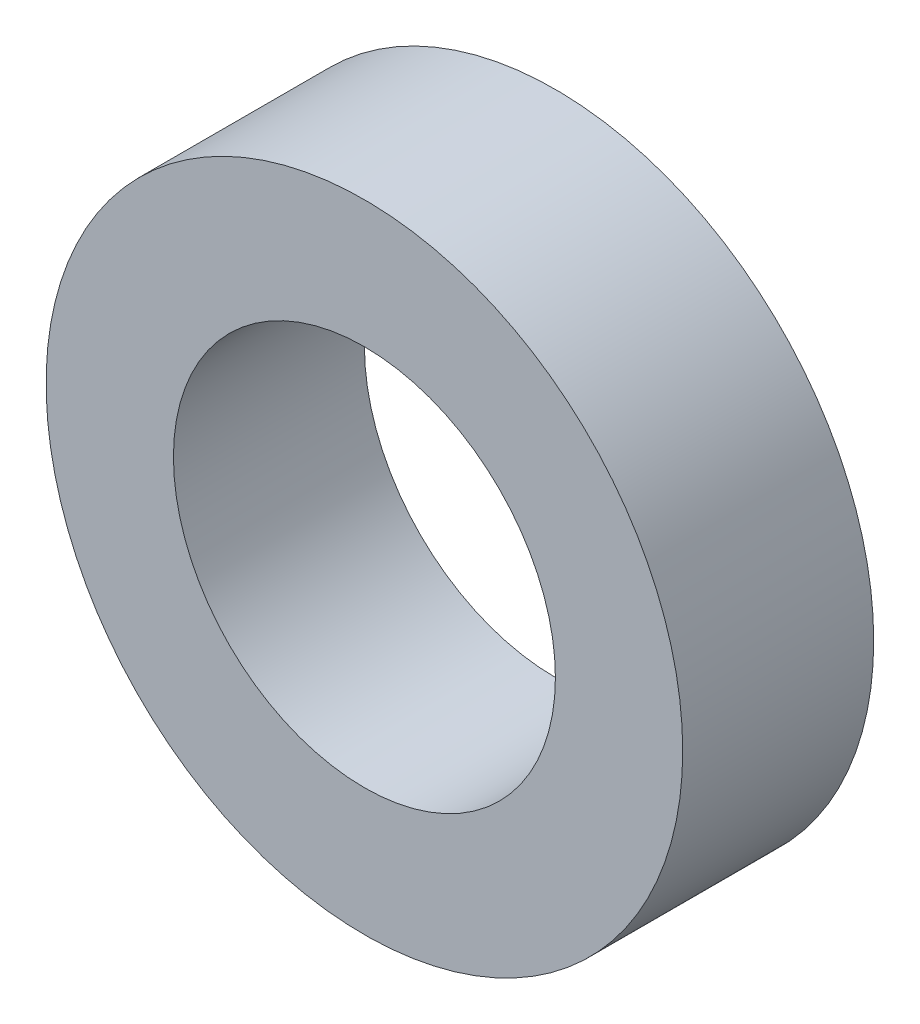
SolidWorks part; units mm, degrees
ref_plane "Plan1" through (0, 0, 0) normal (0, 0, 1) x (1, 0, 0)
ref_plane "Plan2" through (0, 0, 0) normal (0, 1, 0) x (1, 0, 0)
ref_plane "Plan3" through (0, 0, 0) normal (1, 0, 0) x (0, 0, -1)
sketch "Esquisse1" plane through (0, 0, 0) normal (0, 0, 1) x (1, 0, 0)
  circle A0 centre (0, 0) radius 10
  circle A1 centre (0, 0) radius 6
  dimension "D1" = 12
  dimension "D2" = 20
extrude "Base-Extrusion" add sketch "Esquisse1" along normal blind 6
